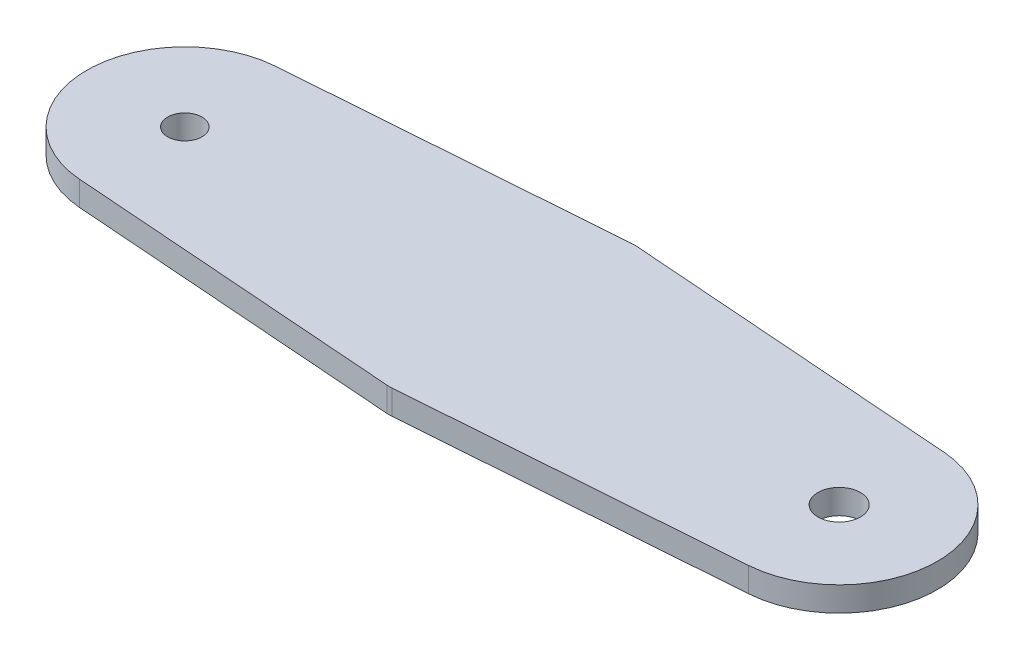
SolidWorks part; units mm, degrees
material "ABS"
ref_plane "前视基准面" through (0, 0, 0) normal (0, 0, 1) x (1, 0, 0)
ref_plane "上视基准面" through (0, 0, 0) normal (0, 1, 0) x (1, 0, 0)
ref_plane "右视基准面" through (0, 0, 0) normal (1, 0, 0) x (0, 0, -1)
other "Configuration Table"
sketch "草图1" plane through (0, 0, 0) normal (0, 1, 0) x (1, 0, 0)
  line L0 (0, 0) -> (80, 0) construction
  line L4 (40, 15) -> (80.8877, 11.9671)
  line L5 (-0.8877, -11.9671) -> (40, -15)
  line L6 (40, -15) -> (80.8877, -11.9671)
  line L7 (-0.8877, 11.9671) -> (40, 15)
  line L8 (40, 0) -> (40, 15) construction
  line L9 (40, -15) -> (40, 0) construction
  circle A0 centre (0, 0) radius 2.1
  circle A1 centre (80, 0) radius 2.6
  arc A2 (-0.8877, 11.9671) -> (-0.8877, -11.9671) centre (0, 0) ccw
  arc A3 (80.8877, 11.9671) -> (80.8877, -11.9671) centre (80, 0) cw
  dimension "D1" = 80
  dimension "D2" = 4.2
  dimension "D3" = 5.2
  dimension "D4" = 12
  dimension "D5" = 12
  dimension "D6" = 30
extrude "凸台-拉伸1" add sketch "草图1" along normal blind 3 contours A0 | L7 L4 A3 L6 L5 A2 | A1
fillet "圆角1" radius 4 2 edges at (40, 1.5, 15) (40, 1.5, -15)
